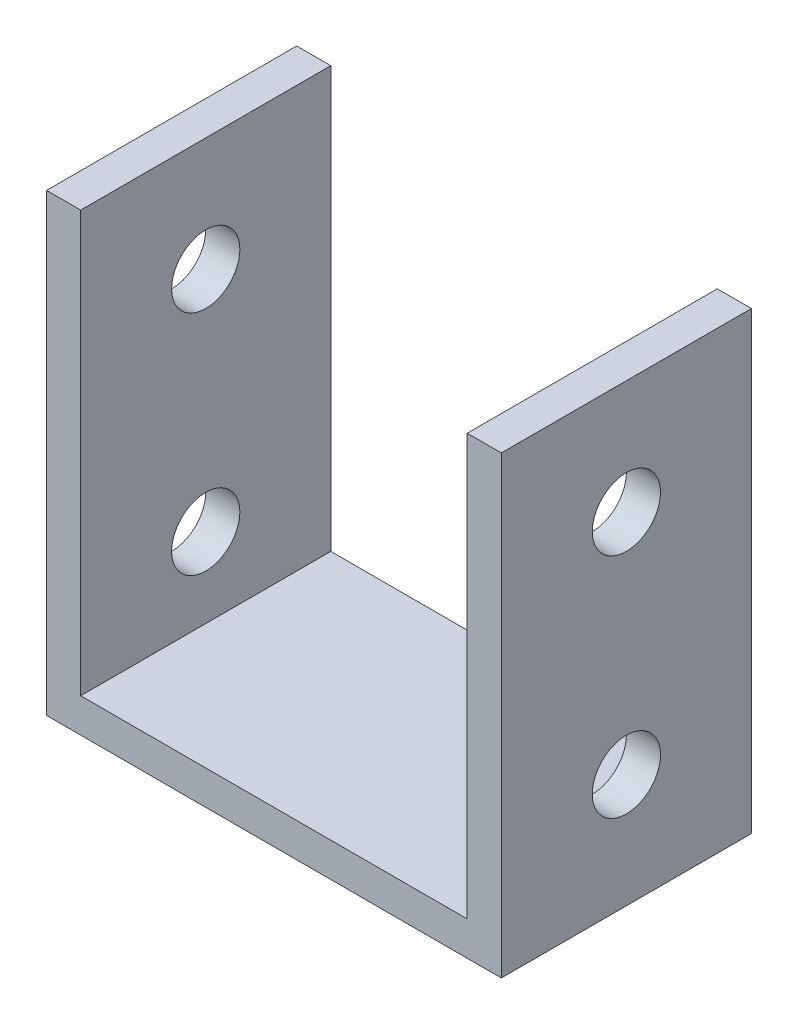
SolidWorks part; units mm, degrees
ref_plane "Plan de face" through (0, 0, 0) normal (0, 0, 1) x (1, 0, 0)
ref_plane "Plan de dessus" through (0, 0, 0) normal (0, 1, 0) x (1, 0, 0)
ref_plane "Plan de droite" through (0, 0, 0) normal (1, 0, 0) x (0, 0, -1)
sketch "Esquisse1" plane through (0, 0, 0) normal (0, 0, 1) x (1, 0, 0)
  line L0 (-25.6132, 22.4991) -> (-25.6132, 2.4991)
  line L1 (-25.6132, 2.4991) -> (-5.6132, 2.4991)
  line L2 (-5.6132, 2.4991) -> (-5.6132, 22.4991)
  line L3 (-5.6132, 22.4991) -> (-7.1132, 22.4991)
  line L4 (-7.1132, 22.4991) -> (-7.1132, 3.9991)
  line L5 (-7.1132, 3.9991) -> (-24.1132, 3.9991)
  line L6 (-24.1132, 3.9991) -> (-24.1132, 22.4991)
  line L7 (-24.1132, 22.4991) -> (-25.6132, 22.4991)
  dimension "D1" = 1.5
  dimension "D2" = 1.5
  dimension "D3" = 1.5
  dimension "D4" = 20
  dimension "D5" = 20
  dimension "D6" = 20
extrude "Extrusion1" add sketch "Esquisse1" along normal blind 11
sketch "Esquisse3" plane through (-5.6132, 0, 0) normal (1, 0, 0) x (0, 0, -1)
  line L0 (-5.5, 7.4991) -> (-5.5, 17.4991) construction
  line L1 (-11, 22.4991) -> (0, 22.4991) construction
  line L2 (0, 2.4991) -> (0, 22.4991) construction
  circle A0 centre (-5.5, 7.4991) radius 1.5
  circle A1 centre (-5.5, 17.4991) radius 1.5
  dimension "D2" = 5
  dimension "D1" = 10
  dimension "D3" = 5.5
extrude "Extrusion3" cut sketch "Esquisse3" against normal through all
